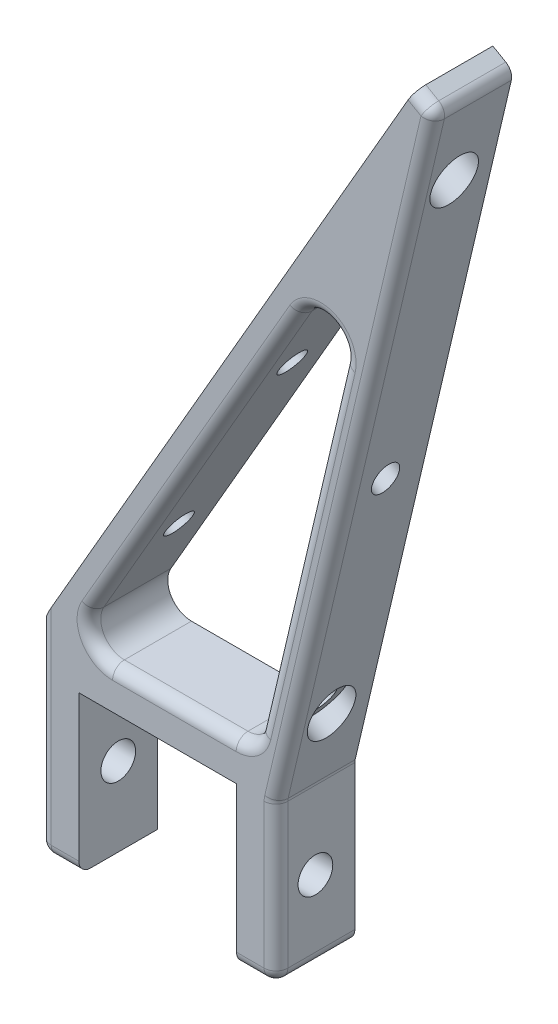
SolidWorks part; units mm, degrees
material "ABS"
ref_plane "Front Plane" through (0, 0, 0) normal (0, 0, 1) x (1, 0, 0)
ref_plane "Top Plane" through (0, 0, 0) normal (0, 1, 0) x (1, 0, 0)
ref_plane "Right Plane" through (0, 0, 0) normal (1, 0, 0) x (0, 0, -1)
sketch "Sketch1" plane through (0, 0, 0) normal (0, 0, 1) x (1, 0, 0)
  line L0 (-10, -20) -> (-10, 0)
  line L1 (-10, 0) -> (10, 0)
  line L2 (10, 0) -> (10, -20)
  line L3 (10, -20) -> (15, -20)
  line L4 (15, -20) -> (15, 0)
  line L5 (15, 0) -> (35.1015, 85.7704)
  line L6 (32.5, 87.2724) -> (-15, 5)
  line L7 (-15, 5) -> (-15, -20)
  line L8 (-15, -20) -> (-10, -20)
  line L9 (32.5, 87.2724) -> (35.1015, 85.7704)
  dimension "D1" = 5
  dimension "D2" = 20
  dimension "D3" = 20
  dimension "D4" = 166.81
  dimension "D5" = 150
  dimension "D6" = 20
  dimension "D7" = 25
  dimension "D8" = 95
extrude "Boss-Extrude1" add sketch "Sketch1" along normal blind 10
sketch "Sketch2" plane through (0, 0, 10) normal (0, 0, 1) x (1, 0, 0)
  line L0 (-10.9175, 5) -> (28.2148, 72.7791)
  line L1 (28.2148, 72.7791) -> (12.3298, 5)
  line L2 (12.3298, 5) -> (-10.9175, 5)
  line L3 (-10, 0) -> (10, 0) construction
  line L5 (15, 0) -> (35.1015, 85.7704) construction
  line L6 (32.5, 87.2724) -> (-15, 5) construction
  dimension "D1" = 5
  dimension "D2" = 3.7406
  dimension "D3" = 3.5356
extrude "Cut-Extrude1" cut sketch "Sketch2" against normal through all
fillet "Fillet1" radius 3 3 edges at (-10.9175, 5, 5) (12.3298, 5, 5) (28.2148, 72.7791, 5)
fillet "Fillet2" radius 1.5 16 edges at (35.1015, 85.7704, 5) (-15, -7.5, 10) (33.8007, 86.5214, 10) (25.0507, 42.8852, 10) (15, -10, 10) (12.5, -20, 10) (-12.5, -20, 10) (21.7651, 56.485, 10) (4.8718, 32.3478, 10) (-8.3194, 6.5, 10) (2.1151, 5, 10) (11.8153, 5.6491, 10) (18.2272, 30.1633, 10) (15, 0, 5) (15, -20, 5) (-15, -20, 5)
sketch "Sketch3" plane through (-15, 0, 0) normal (-1, 0, 0) x (0, 0, 1)
  line L0 (0, 5) -> (0, -18.5) construction
  line L1 (8.5, -20) -> (0, -20) construction
  circle A0 centre (5, -10) radius 2.2
  dimension "D1" = 5
  dimension "D2" = 10
  dimension "D3" = 4.4
extrude "Cut-Extrude2" cut sketch "Sketch3" against normal through all
sketch "Sketch4" plane through (-13.4151, 7.7452, 0) normal (-0.866, 0.5, 0) x (0, 0, 1)
  line L0 (10, 23.3264) -> (0, 23.3264) construction
  line L1 (10, 90.3301) -> (10, -0.1699) construction
  line L2 (0, 91.8301) -> (0, -3.1699) construction
  line L3 (5, 16.0989) -> (5, 23.3264) construction
  line L4 (8.5, 91.8301) -> (0, 91.8301) construction
  circle A0 centre (5, 81.3301) radius 1.75
  circle A1 centre (5, 44.8301) radius 1.75
  circle A2 centre (5, 16.0989) radius 1.75
  dimension "D1" = 3.5
  dimension "D2" = 10.5
  dimension "D3" = 36.5
  dimension "D4" = 28.7312
extrude "Cut-Extrude3" cut sketch "Sketch4" against normal through all
sketch "Sketch5" plane through (-13.4805, 7.6318, 0) normal (0.866, -0.5, 0) x (0, 0, -1)
  circle A0 centre (-5, 81.4611) radius 3
  dimension "D1" = 6
extrude "Cut-Extrude4" cut sketch "Sketch5" along normal through all from offset 3
sketch "Sketch6" plane through (-13.4151, 7.7452, 0) normal (-0.866, 0.5, 0) x (0, 0, 1)
  circle A0 centre (5, 16.0989) radius 3
  dimension "D1" = 6
extrude "Cut-Extrude5" cut sketch "Sketch6" against normal through all from offset 24.38
